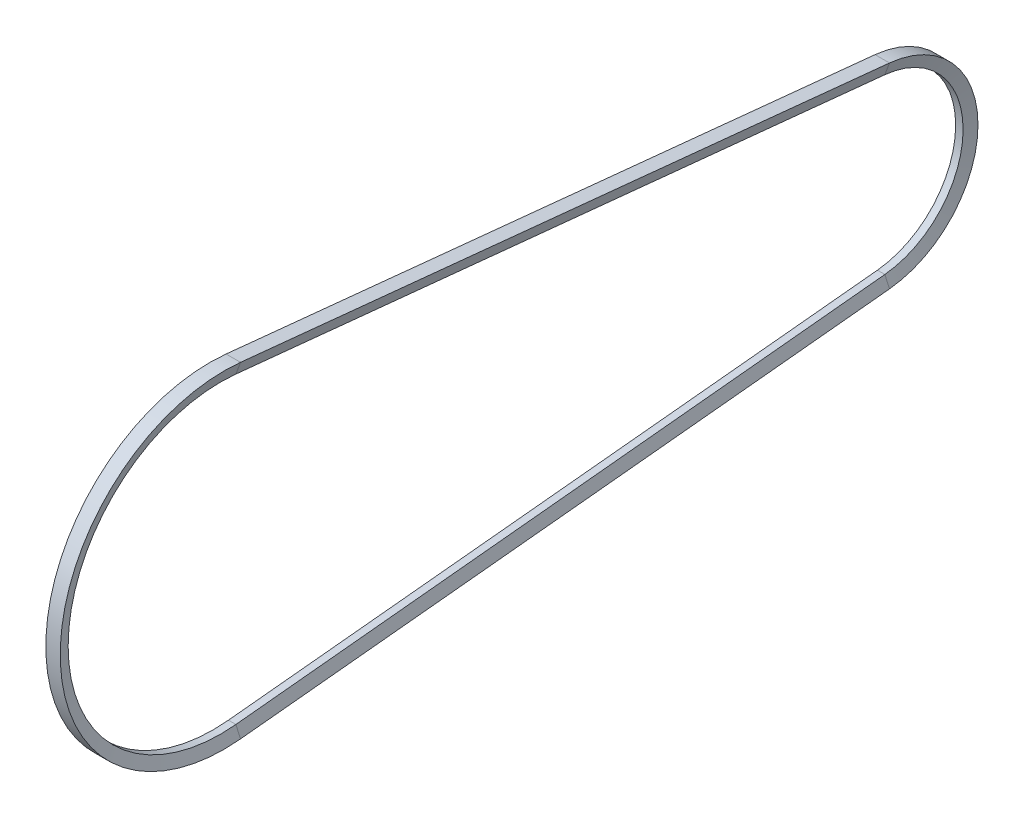
SolidWorks part; units mm, degrees
ref_plane "前视基准面" through (0, 0, 0) normal (0, 0, 1) x (1, 0, 0)
ref_plane "上视基准面" through (0, 0, 0) normal (0, 1, 0) x (1, 0, 0)
ref_plane "右视基准面" through (0, 0, 0) normal (1, 0, 0) x (0, 0, -1)
sketch "草图1" plane through (0, 0, 0) normal (1, 0, 0) x (0, 0, -1)
  line L0 (12.5, 124.3734) -> (507.5, 74.6241)
  line L1 (12.5, -124.3734) -> (507.5, -74.6241)
  line L2 (0, 0) -> (500, 0) construction
  arc A0 (12.5, 124.3734) -> (12.5, -124.3734) centre (0, 0) ccw
  arc A1 (507.5, -74.6241) -> (507.5, 74.6241) centre (500, 0) ccw
  dimension "D1" = 125
  dimension "D2" = 75
  dimension "D3" = 500
sketch "草图2" plane through (0, 0, 0) normal (0, 0, 1) x (1, 0, 0)
  line L0 (-5.5, 125) -> (5.5, 125)
  line L1 (5.5, 125) -> (2.8401, 116.3)
  line L2 (2.8401, 116.3) -> (-2.8401, 116.3)
  line L3 (-2.8401, 116.3) -> (-5.5, 125)
  line L4 (0, 116.3) -> (0, 125) construction
  line L5 (0, -125) -> (0, 125) construction
  dimension "D1" = 11
  dimension "D2" = 8.7
  dimension "D3" = 34
sweep "扫描1" add profiles "草图2" path "草图1"
equation "\"D3@草图1\" = \"D1@距离1@实心轮_实心轮.Assembly\""
equation "\"D3@草图1\" = \"D1@距离1@实心轮_孔板轮.Assembly\""
equation "\"D3@草图1\" = \"D1@距离1@实心轮_辐板轮.Assembly\""
equation "\"D3@草图1\" = \"D1@距离1@辐板轮_辐板轮.Assembly\""
equation "\"D3@草图1\" = \"D1@距离1@孔板轮_辐板轮.Assembly\""
equation "\"D1@草图2\" = \"bd@草图1@小带轮_实心轮.Part\" "
equation "\"D1@草图2\" = \"bd@草图1@大带轮_辐板轮.Part\" "
equation "\"D2@草图2\" = \"hf@草图1@小带轮_实心轮.Part\" "
equation "\"D2@草图2\" = \"hf@草图1@大带轮_辐板轮.Part\" "
equation "\"D3@草图2\" = \"槽轮角@草图1@小带轮_实心轮.Part\" "
equation "\"D3@草图2\" = \"槽轮角@草图1@大带轮_辐板轮.Part\" "
equation "\"D2@草图1\" = \"dd@草图1@小带轮_实心轮.Part\"/2"
equation " \"D2@草图1\" = \"dd@草图1@小带轮_辐板轮.Part\"/2"
equation "\"D2@草图1\" = \"dd@草图1@小带轮_辐板轮.Part\"/2  "
equation "\"D1@草图1\" = \"dd@草图1@大带轮_实心轮.Part\" /2"
equation "\"D1@草图1\" = \"dd@草图1@大带轮_辐板轮.Part\" /2"
